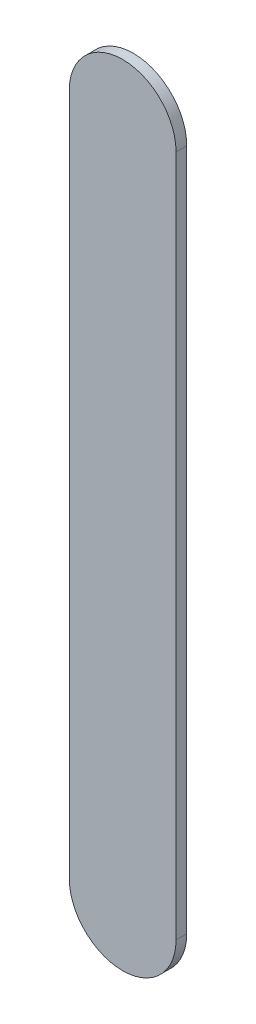
SolidWorks part; units mm, degrees
ref_plane "Front Plane" through (0, 0, 0) normal (0, 0, 1) x (1, 0, 0)
ref_plane "Top Plane" through (0, 0, 0) normal (0, 1, 0) x (1, 0, 0)
ref_plane "Right Plane" through (0, 0, 0) normal (1, 0, 0) x (0, 0, -1)
sketch "Sketch1" plane through (0, 0, 0) normal (0, 0, 1) x (1, 0, 0)
  line L0 (0, 0) -> (0, 63.9) construction
  line L1 (-5, 0) -> (-5, 63.9)
  line L2 (5, 0) -> (5, 63.9)
  arc A0 (-5, 0) -> (5, 0) centre (0, 0) ccw
  arc A1 (5, 63.9) -> (-5, 63.9) centre (0, 63.9) ccw
  point P3 (0, 31.95)
  dimension "D1" = 63.9
  dimension "D2" = 10
extrude "Boss-Extrude1" add sketch "Sketch1" along normal blind 1
